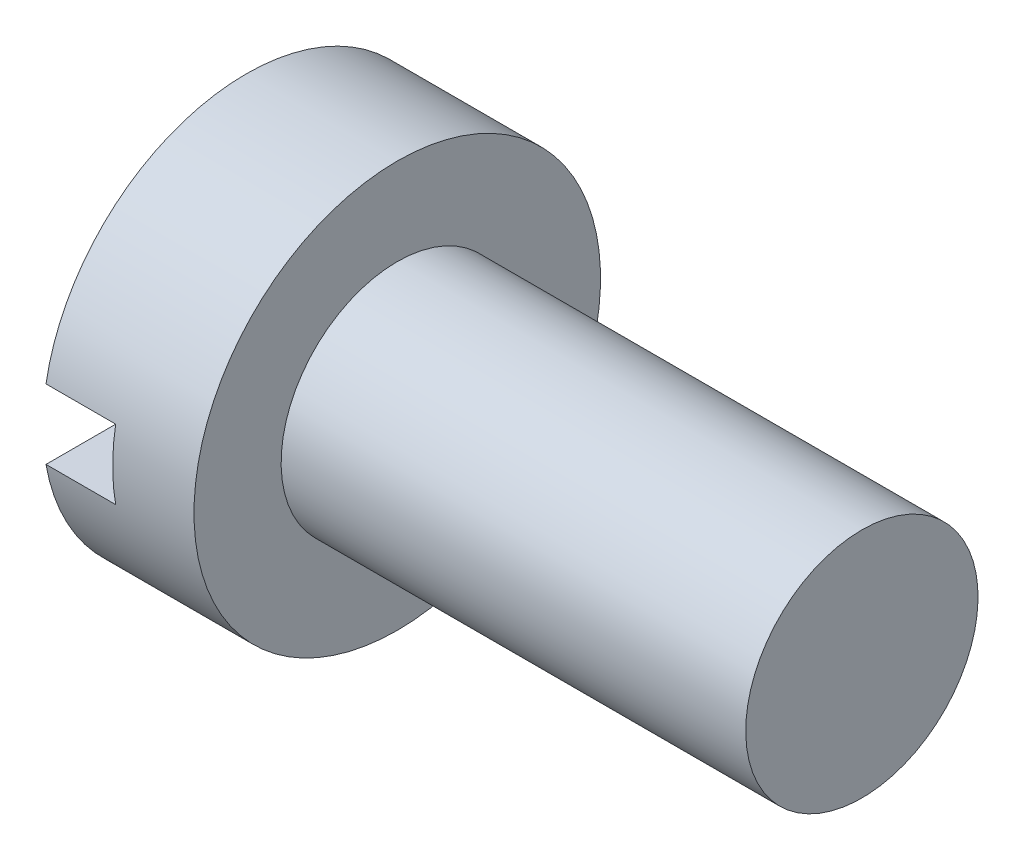
SolidWorks part; units mm, degrees
material "Plain Carbon Steel"
ref_plane "Front Plane" through (0, 0, 0) normal (0, 0, 1) x (1, 0, 0)
ref_plane "Top Plane" through (0, 0, 0) normal (0, 1, 0) x (1, 0, 0)
ref_plane "Right Plane" through (0, 0, 0) normal (1, 0, 0) x (0, 0, -1)
sketch "Sketch1" plane through (0, 0, 0) normal (0, 0, 1) x (1, 0, 0)
  line L0 (0, 0) -> (0, 3.5)
  line L1 (0, 3.5) -> (2.6, 3.5)
  line L2 (2.6, 3.5) -> (2.6, 2)
  line L3 (2.6, 2) -> (10.6, 2)
  line L4 (10.6, 2) -> (10.6, 0)
  line L5 (10.6, 0) -> (0, 0) construction
  line L6 (0, 0) -> (10.6, 0)
  dimension "D1" = 4
  dimension "D2" = 8
  dimension "D3" = 7
  dimension "D4" = 2.6
revolve "Revolve1" add sketch "Sketch1" angle 360 about L5
sketch "Sketch2" plane through (0, 0, 0) normal (-1, 0, 0) x (0, 0, 1)
  line L0 (3.5, 0) -> (-3.5, 0) construction
  line L1 (-3.5, 0.6) -> (3.5, 0.6)
  line L2 (-3.5, 0.6) -> (-3.5, -0.6)
  line L3 (-3.5, -0.6) -> (3.5, -0.6)
  line L4 (3.5, 0.6) -> (3.5, -0.6)
  circle A0 centre (0, 0) radius 3.5 construction
  dimension "D1" = 1.2
extrude "Cut-Extrude1" cut sketch "Sketch2" against normal blind 1.2
